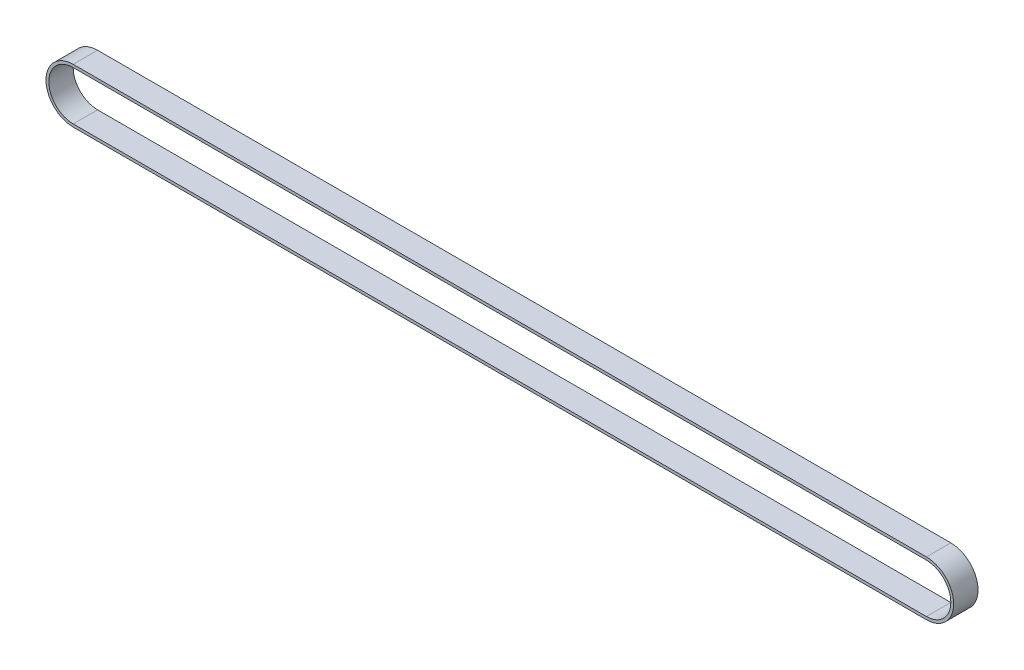
SolidWorks part; units mm, degrees
ref_plane "Front" through (0, 0, 0) normal (0, 0, 1) x (1, 0, 0)
ref_plane "Top" through (0, 0, 0) normal (0, 1, 0) x (1, 0, 0)
ref_plane "Right" through (0, 0, 0) normal (1, 0, 0) x (0, 0, -1)
sketch "Sketch1" plane through (0, 0, 0) normal (0, 0, 1) x (1, 0, 0)
  line L0 (1400, -40.055) -> (0, -40.055)
  line L1 (0, 40.055) -> (1400, 40.055)
  line L2 (0, -44.655) -> (1400, -44.655)
  line L3 (1400, 44.655) -> (0, 44.655)
  arc A0 (0, -40.055) -> (0, 40.055) centre (0, 0) cw
  arc A1 (1400, 40.055) -> (1400, -40.055) centre (1400, 0) cw
  arc A2 (1400, -44.655) -> (1400, 44.655) centre (1400, 0) ccw
  arc A3 (0, 44.655) -> (0, -44.655) centre (0, 0) ccw
  dimension "D1" = 40.055
  dimension "D2" = 44.655
  dimension "D3" = 1400
extrude "Boss-Extrude1" add sketch "Sketch1" along normal blind 40
